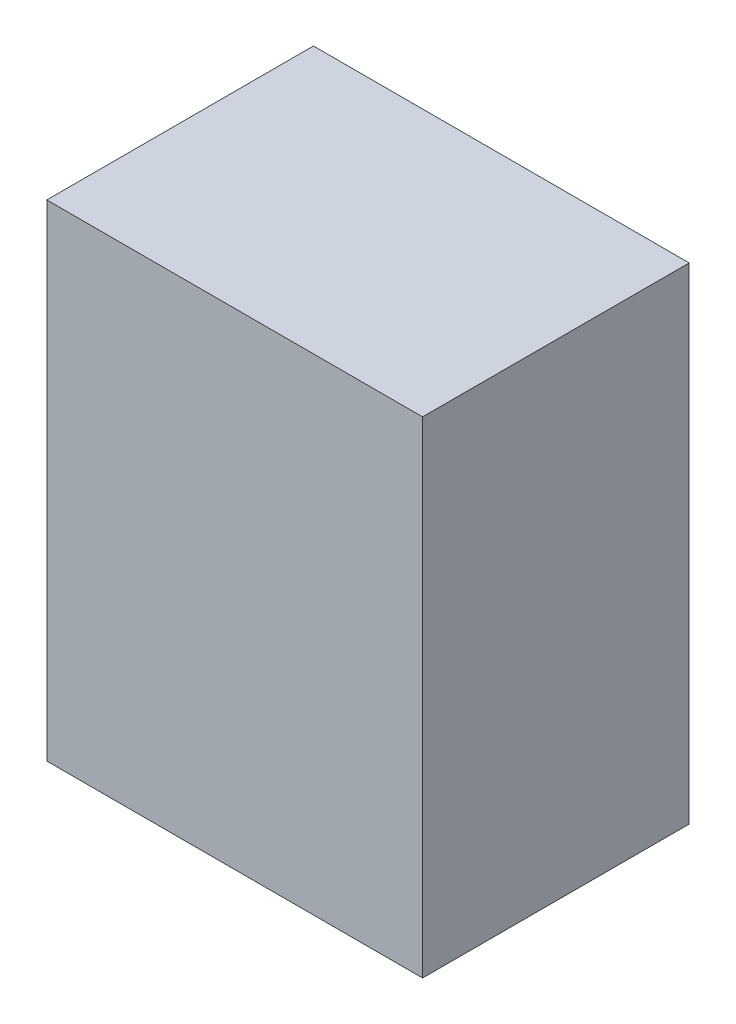
SolidWorks part; units mm, degrees
ref_plane "Front Plane" through (0, 0, 0) normal (0, 0, 1) x (1, 0, 0)
ref_plane "Top Plane" through (0, 0, 0) normal (0, 1, 0) x (1, 0, 0)
ref_plane "Right Plane" through (0, 0, 0) normal (1, 0, 0) x (0, 0, -1)
sketch "Sketch1" plane through (0, 0, 0) normal (0, 0, 1) x (1, 0, 0)
  line L0 (-3.2893, -1.5502) -> (3.2639, -1.5502)
  line L1 (3.2639, -1.5502) -> (3.2639, 6.925)
  line L2 (3.2639, 6.925) -> (-3.2893, 6.925)
  line L3 (-3.2893, 6.925) -> (-3.2893, -1.5502)
extrude "Component_Outline" add sketch "Sketch1" along normal blind 4.65 separate body
sketch3d "3DSketch1"
  line L0 (0, 0, 0) -> (1, 0, 0)
  line L1 (0, 0, 0) -> (0, 1, 0)
  line L2 (0, 0, 0) -> (0, 0, 1)
  point P0 (0, 0, 0)
